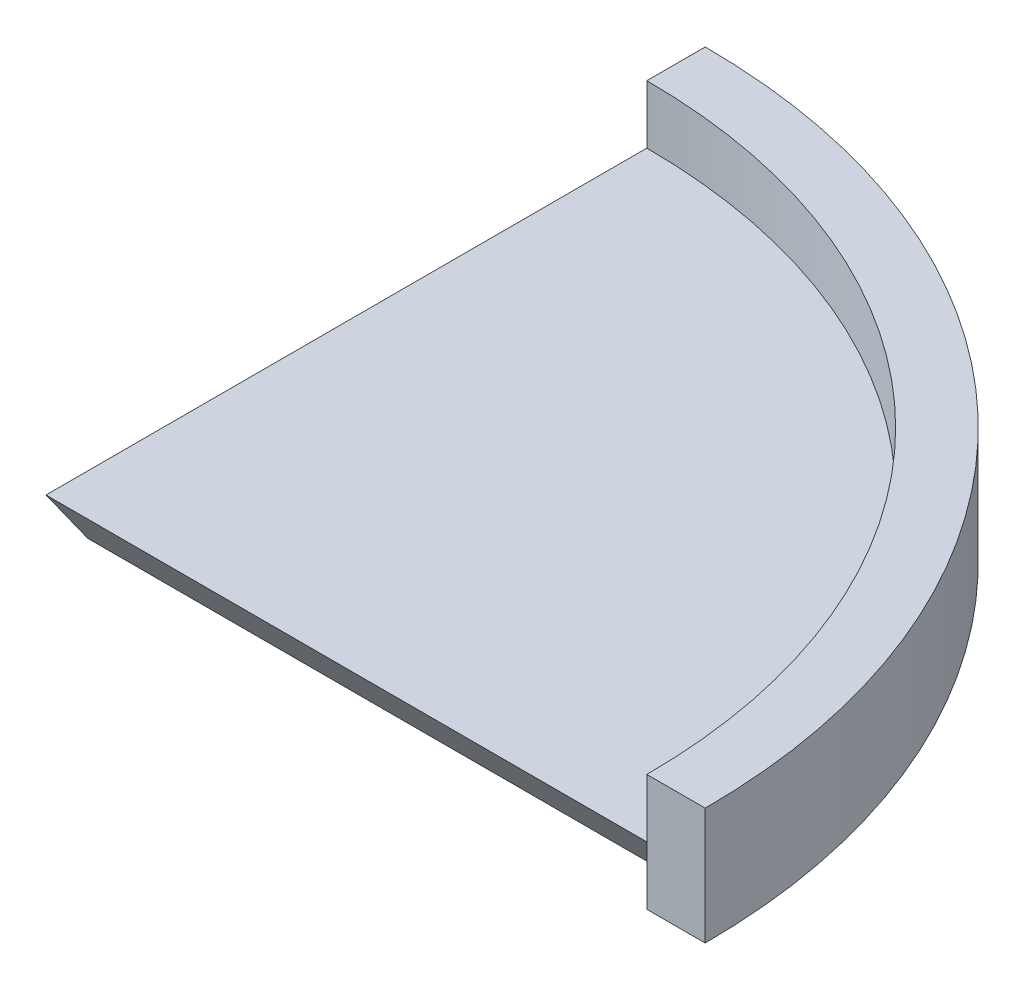
SolidWorks part; units mm, degrees
material "Pino"
ref_plane "Alzado" through (0, 0, 0) normal (0, 0, 1) x (1, 0, 0)
ref_plane "Planta" through (0, 0, 0) normal (0, 1, 0) x (1, 0, 0)
ref_plane "Vista lateral" through (0, 0, 0) normal (1, 0, 0) x (0, 0, -1)
sketch "Croquis3" plane through (0, 0, 0) normal (1, 0, 0) x (0, 0, -1)
  line L1 (-925.4161, 408.7628) -> (-530.4161, 408.7628)
  line L2 (-925.4161, 408.7628) -> (-925.4161, 373.7628)
  line L3 (-925.4161, 373.7628) -> (-530.4161, 373.7628)
  line L4 (-530.4161, 408.7628) -> (-530.4161, 373.7628)
  dimension "D1" = 395
  dimension "D2" = 35
revolve "Revolución1" add sketch "Croquis3" angle 90 about L2
sketch "Croquis5" plane through (0, 0, 0) normal (1, 0, 0) x (0, 0, -1)
  line L1 (-530.4161, 408.7628) -> (-565.4161, 408.7628)
  line L2 (-530.4161, 408.7628) -> (-530.4161, 443.7628)
  line L3 (-530.4161, 443.7628) -> (-565.4161, 443.7628)
  line L4 (-565.4161, 408.7628) -> (-565.4161, 443.7628)
  dimension "D1" = 35
  dimension "D2" = 35
revolve "Revolución3" add sketch "Croquis5" angle 90 about axis through (0, 408.7628, 925.4161) along (0, -1, 0)
sketch "Croquis12" plane through (0, 0, 925.4161) normal (0, 0, 1) x (1, 0, 0)
  line L1 (360, 408.7628) -> (0, 408.7628)
  line L2 (360, 408.7628) -> (360, 373.7628)
  line L3 (360, 373.7628) -> (0, 373.7628)
  line L4 (0, 408.7628) -> (0, 373.7628)
extrude "Saliente-Extruir1" [suppressed] add sketch "Croquis12" along normal blind 300
sketch "Croquis15" [suppressed] plane through (360, 0, 0) normal (1, 0, 0) x (0, 0, -1)
  line L1 (-1225.4161, 408.7628) -> (-925.4161, 408.7628)
  line L2 (-1225.4161, 408.7628) -> (-1225.4161, 373.7628)
  line L5 (-1225.4161, 373.7628) -> (-925.4161, 408.7628)
extrude "Cortar-Extruir2" [suppressed] cut sketch "Croquis15" against normal blind 360
sketch "Croquis17" plane through (0, 0, 0) normal (-1, 0, 0) x (0, 0, 1)
  line L0 (925.4161, 373.7628) -> (900.4161, 373.7628)
  line L1 (925.4161, 373.7628) -> (530.4161, 373.7628) construction
  line L2 (900.4161, 373.7628) -> (925.4161, 408.7628)
  line L3 (925.4161, 408.7628) -> (925.4161, 373.7628)
  dimension "D1" = 25
extrude "Cortar-Extruir5" cut sketch "Croquis17" against normal blind 360
